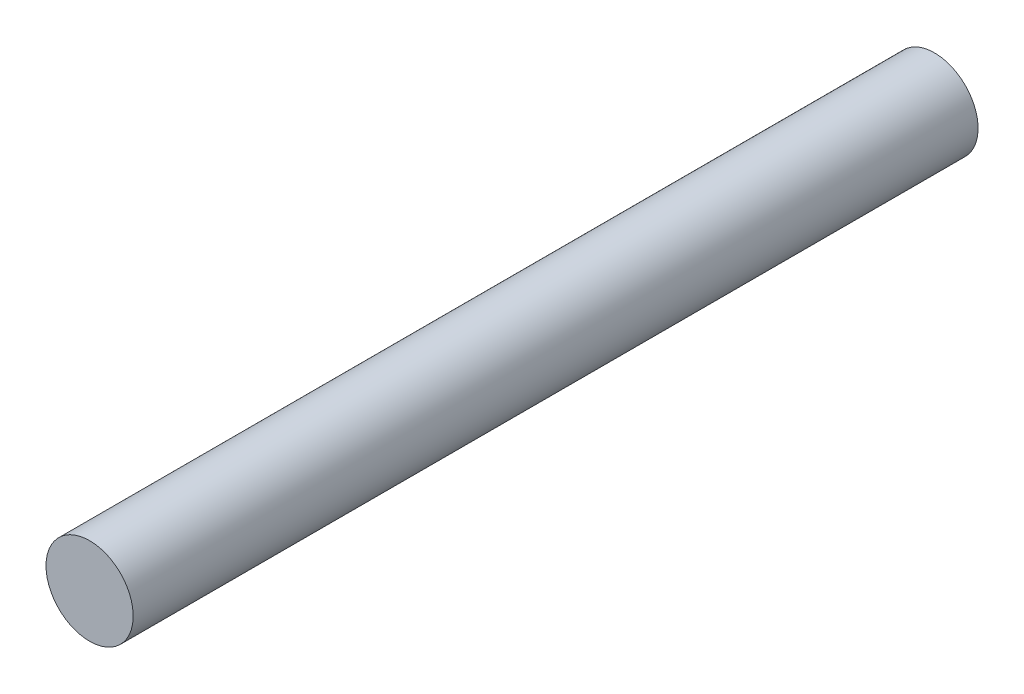
SolidWorks part; units mm, degrees
ref_plane "Front Plane" through (0, 0, 0) normal (0, 0, 1) x (1, 0, 0)
ref_plane "Top Plane" through (0, 0, 0) normal (0, 1, 0) x (1, 0, 0)
ref_plane "Right Plane" through (0, 0, 0) normal (1, 0, 0) x (0, 0, -1)
sketch "Sketch1" plane through (0, 0, 0) normal (0, 0, 1) x (1, 0, 0)
  circle A0 centre (0, 0) radius 6.35
  dimension "D1" = 12.7
extrude "Boss-Extrude1" add sketch "Sketch1" along normal blind 123.063
